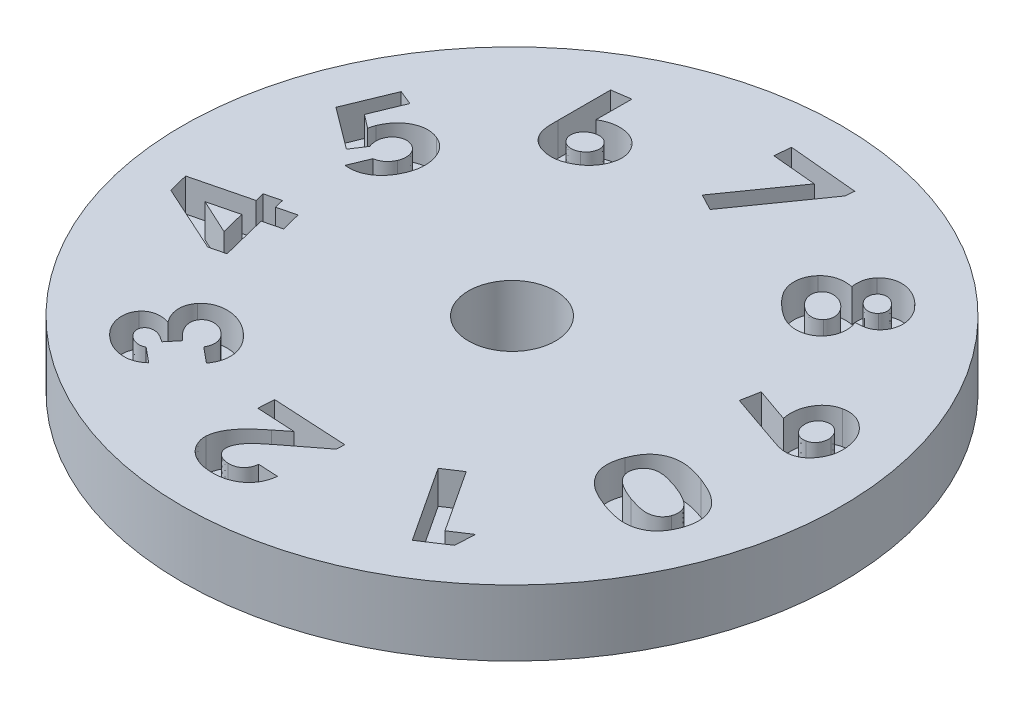
SolidWorks part; units mm, degrees
ref_plane "Front Plane" through (0, 0, 0) normal (0, 0, 1) x (1, 0, 0)
ref_plane "Top Plane" through (0, 0, 0) normal (0, 1, 0) x (1, 0, 0)
ref_plane "Right Plane" through (0, 0, 0) normal (1, 0, 0) x (0, 0, -1)
sketch "Sketch1" plane through (0, 0, 0) normal (0, 1, 0) x (1, 0, 0)
  circle A0 centre (0, 0) radius 12.7
  dimension "D1" = 25.4
extrude "Boss-Extrude1" add sketch "Sketch1" along normal blind 2.54
sketch "Sketch2" plane through (0, 2.54, 0) normal (0, 1, 0) x (1, 0, 0)
  circle A0 centre (0, 0) radius 1.6764
  dimension "D1" = 3.3528
extrude "Cut-Extrude1" cut sketch "Sketch2" against normal blind 2.54
sketch "Sketch5" plane through (0, 2.54, 0) normal (0, 1, 0) x (1, 0, 0)
  text T0 "<b>0 1 2 3 4 5 6 7 8 9</b>" font "Century Gothic" height 3.5
extrude "Cut-Extrude4" cut sketch "Sketch5" against normal blind 1.27
